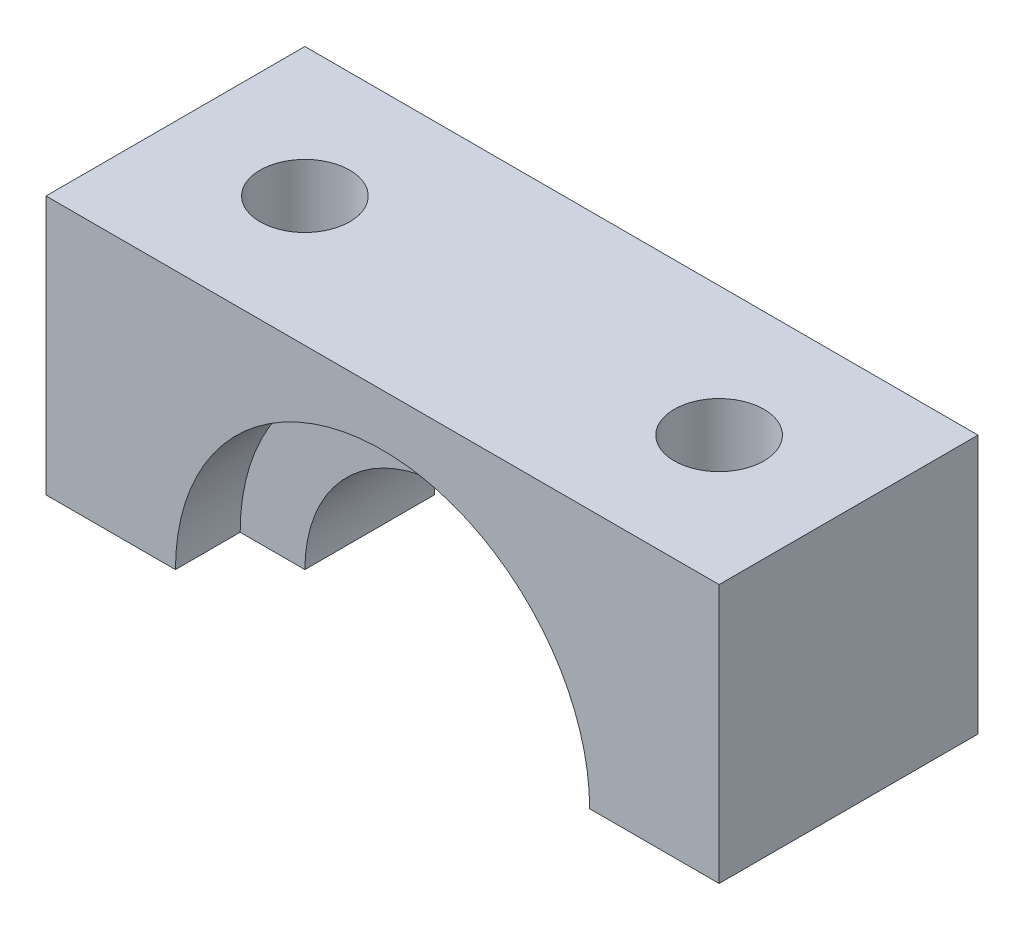
SolidWorks part; units mm, degrees
ref_plane "Plano frontal" through (0, 0, 0) normal (0, 0, 1) x (1, 0, 0)
ref_plane "Plano superior" through (0, 0, 0) normal (0, 1, 0) x (1, 0, 0)
ref_plane "Plano direito" through (0, 0, 0) normal (1, 0, 0) x (0, 0, -1)
sketch "Esboço1" plane through (0, 0, 0) normal (0, 0, 1) x (1, 0, 0)
  line L0 (-5.5, 0) -> (-13, 0)
  line L1 (-13, 0) -> (-13, 10)
  line L2 (-13, 10) -> (13, 10)
  line L3 (13, 10) -> (13, 0)
  line L4 (13, 0) -> (5.5, 0)
  arc A0 (5.5, 0) -> (-5.5, 0) centre (0, 0) ccw
  dimension "D1" = 5.5
  dimension "D2" = 26
  dimension "D3" = 10
extrude "Ressalto-extrusão1" add sketch "Esboço1" along normal mid plane 5
sketch "Esboço3" plane through (0, 0, 0) normal (0, 0, 1) x (1, 0, 0)
  line L0 (-13, 10) -> (-13, 0)
  line L1 (-13, 0) -> (-8, 0)
  line L2 (8, 0) -> (13, 0)
  line L3 (13, 0) -> (13, 10)
  line L4 (13, 10) -> (-13, 10)
  arc A0 (8, 0) -> (-8, 0) centre (0, 0) ccw
  point P7 (0, 0)
  point P13 (0, 0)
  dimension "D1" = 8
extrude "Ressalto-extrusão2" add sketch "Esboço3" along normal mid plane 10
sketch "Esboço2" plane through (0, 0, 0) normal (0, -1, 0) x (1, 0, 0)
  line L0 (0, 0) -> (0, 9.5392) construction
  line L1 (-5.5, 2.5) -> (-5.5, -2.5) construction
  circle A0 centre (-8, 0) radius 1.7309
  circle A1 centre (8, 0) radius 1.7309
  point P7 (-5.5, 0)
  dimension "D1" = 16
extrude "Corte-extrusão1" cut sketch "Esboço2" against normal blind 15
